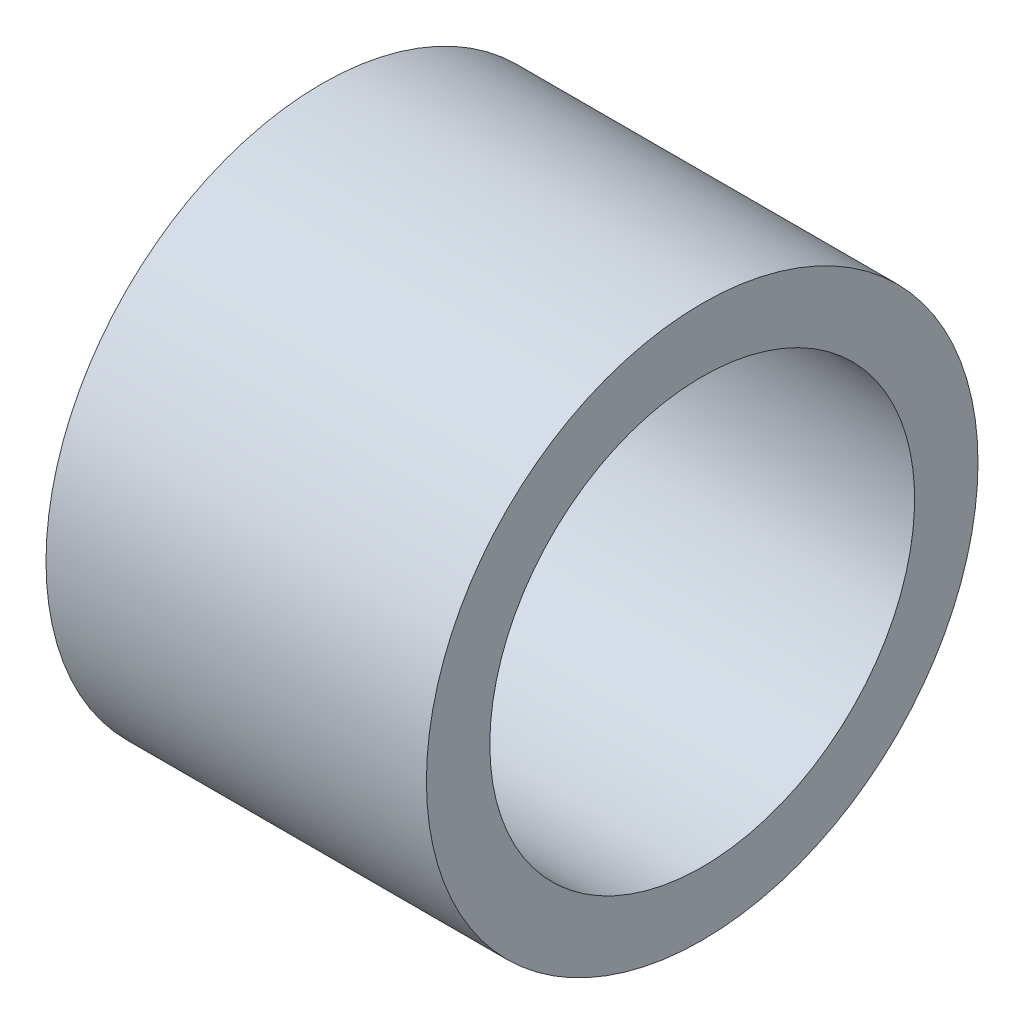
SolidWorks part; units mm, degrees
ref_plane "Front Plane" through (0, 0, 0) normal (0, 0, 1) x (1, 0, 0)
ref_plane "Top Plane" through (0, 0, 0) normal (0, 1, 0) x (1, 0, 0)
ref_plane "Right Plane" through (0, 0, 0) normal (1, 0, 0) x (0, 0, -1)
sketch "Sketch1" plane through (0, 0, 0) normal (0, 0, 1) x (1, 0, 0)
  line L0 (0, 0) -> (19447.1753, 0) construction
  line L1 (0, 3) -> (0, 4.35)
  line L2 (0, 4.35) -> (6, 4.35)
  line L3 (6, 4.35) -> (6, 3.35)
  line L4 (6, 3.35) -> (1, 3.35)
  line L5 (1, 3.35) -> (1, 1)
  line L6 (1, 1) -> (0, 1)
  line L7 (0, 1) -> (-1, 1)
  line L8 (-1, 1) -> (-1, 2)
  line L9 (-1, 2) -> (0, 3)
  line L10 (0, 3) -> (0, 1) construction
  dimension "D1" = 6.7
  dimension "D2" = 1
  dimension "D3" = 1
  dimension "D4" = 2
  dimension "D5" = 5
  dimension "D6" = 1
  dimension "D7" = 1
  dimension "D8" = 135
revolve "Revolve1" add sketch "Sketch1" angle 360 about L0
